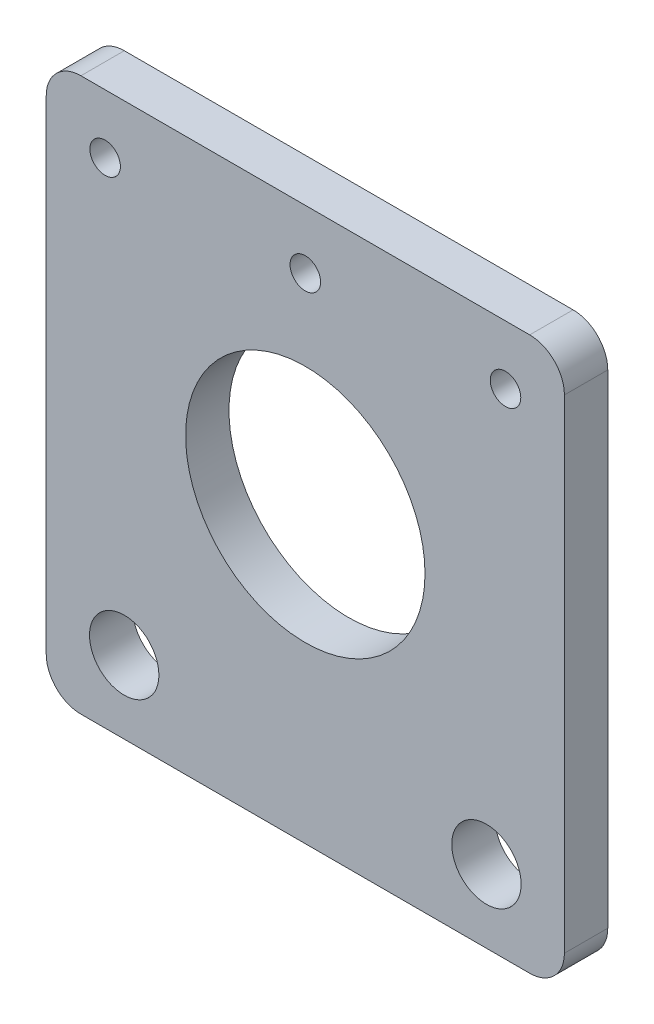
SolidWorks part; units mm, degrees
ref_plane "Front Plane" through (0, 0, 0) normal (0, 0, 1) x (1, 0, 0)
ref_plane "Top Plane" through (0, 0, 0) normal (0, 1, 0) x (1, 0, 0)
ref_plane "Right Plane" through (0, 0, 0) normal (1, 0, 0) x (0, 0, -1)
sketch "Sketch1" plane through (0, 0, 0) normal (0, 0, 1) x (1, 0, 0)
  line L1 (0, 37.9349) -> (37.9349, 37.9349)
  line L2 (0, 37.9349) -> (0, 0)
  line L3 (0, 0) -> (37.9349, 0)
  line L4 (37.9349, 37.9349) -> (37.9349, 0)
  dimension "D1" = 37.9349
extrude "Boss-Extrude1" add sketch "Sketch1" along normal blind 3.175
sketch "Sketch9" plane through (0, 0, 3.175) normal (0, 0, 1) x (1, 0, 0)
  line L0 (33.6232, 37.9349) -> (33.6232, 33.6232) construction
  line L1 (33.6232, 33.6232) -> (37.9349, 33.6232) construction
  line L2 (37.9349, 0) -> (37.9349, 37.9349) construction
  line L3 (37.9349, 37.9349) -> (0, 37.9349) construction
  line L4 (37.9349, 0) -> (37.9349, 37.9349) construction
  line L5 (0, 0) -> (37.9349, 0) construction
  line L6 (4.3117, 37.9349) -> (4.3117, 33.6232) construction
  line L7 (0, 37.9349) -> (0, 0) construction
  line L8 (5.7087, 0) -> (5.7087, 2.7876) construction
  line L9 (0, 2.7876) -> (5.7087, 2.7876) construction
  line L10 (37.9349, 2.7877) -> (32.2263, 2.7877) construction
  line L11 (32.2263, 0) -> (32.2263, 2.7877) construction
  line L12 (4.3117, 33.6232) -> (0, 33.6232) construction
  line L13 (33.6232, 33.6232) -> (4.3117, 33.6232) construction
  line L16 (37.9349, 37.9349) -> (0, 37.9349) construction
  line L25 (18.9674, 37.9349) -> (18.9674, 0) construction
  line L28 (0, 0) -> (37.9349, 0) construction
  line L32 (35.922, 18.9674) -> (2.013, 18.9674) construction
  circle A0 centre (33.6232, 33.6232) radius 1.1176
  circle A1 centre (4.3117, 33.6232) radius 1.1176
  circle A2 centre (5.7087, 2.7876) radius 2.54
  circle A3 centre (32.2263, 2.7877) radius 2.54
  circle A4 centre (18.9674, 33.6232) radius 1.1176
  circle A24 centre (18.9674, 18.9674) radius 8.763
  point P47 (18.9674, 18.9674)
  point P66 (2.0129, 18.9674)
  dimension "D1" = 4.3117
  dimension "D3" = 5.08
  dimension "D4" = 2.2352
  dimension "D5" = 26.5176
  dimension "D8" = 17.526
  dimension "D2" = 2.7877
extrude "Cut-Extrude2" cut sketch "Sketch9" against normal up to surface (3.175 mm away) up to face at (18.9674, 18.9675, 0)
sketch "Sketch11" plane through (0, 0, 0) normal (0, -1, 0) x (1, 0, 0)
  line L0 (37.9349, 3.175) -> (37.9349, 0) construction
  line L1 (0, 3.175) -> (37.9349, 3.175)
  line L2 (0, 3.175) -> (0, 0)
  line L3 (0, 0) -> (37.9349, 0)
  line L4 (37.9349, 3.175) -> (37.9349, 0)
  line L5 (37.9349, 3.175) -> (0, 3.175) construction
extrude "Boss-Extrude2" add sketch "Sketch11" along normal blind 2.54
fillet "Fillet1" radius 2.54 4 edges at (0, -2.54, 1.5875) (37.9349, -2.54, 1.5875) (37.9349, 37.9349, 1.5875) (0, 37.9349, 1.5875)
